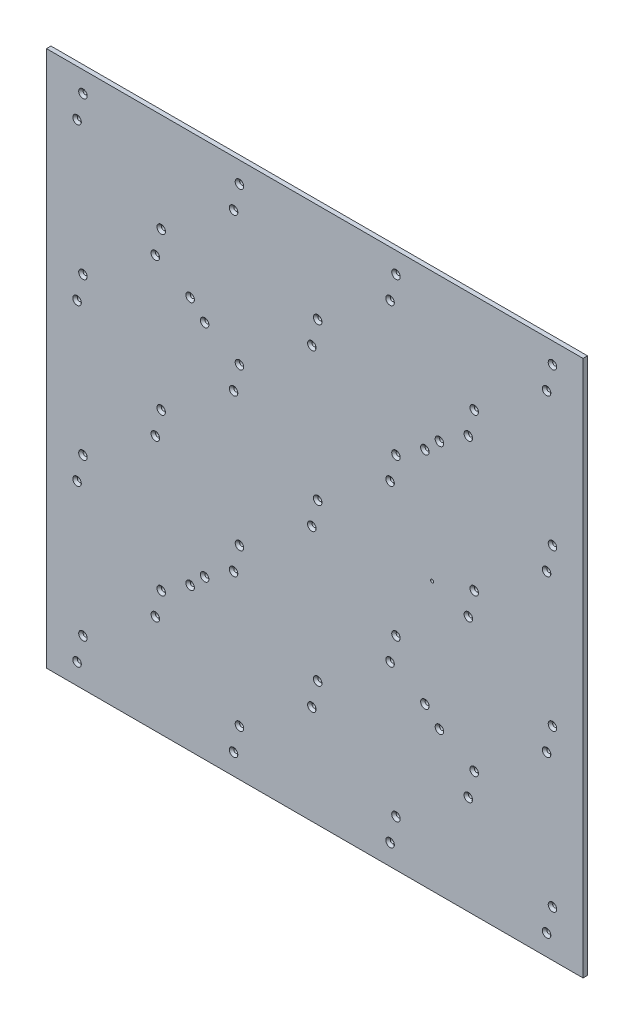
SolidWorks part; units mm, degrees
material "6063-T1"
ref_plane "Front Plane" through (0, 0, 0) normal (0, 0, 1) x (1, 0, 0)
ref_plane "Top Plane" through (0, 0, 0) normal (0, 1, 0) x (1, 0, 0)
ref_plane "Right Plane" through (0, 0, 0) normal (1, 0, 0) x (0, 0, -1)
sketch "Sketch1" plane through (0, 0, 0) normal (0, 0, 1) x (1, 0, 0)
  line L1 (600, -600) -> (-600, -600)
  line L2 (600, -600) -> (600, 600)
  line L3 (600, 600) -> (-600, 600)
  line L4 (-600, -600) -> (-600, 600)
  line L5 (600, -600) -> (-600, 600) construction
  line L6 (600, 600) -> (-600, -600) construction
  point P0 (0, 0)
  dimension "D1" = 1200
  dimension "D2" = 1200
extrude "Boss-Extrude1" add sketch "Sketch1" against normal blind 10 from offset 3
sketch "Sketch2" plane through (0, 0, -7) normal (0, 0, -1) x (-1, 0, 0)
  line L0 (-261.4393, 263.5607) -> (-244.8089, 280.1911) construction
  line L1 (-259.318, 261.4393) -> (-263.5607, 265.682) construction
  line L2 (-268.1434, 303.5257) -> (-221.4743, 256.8566) construction
  circle A1 centre (-278.75, 278.7769) radius 4.5
  circle A2 centre (-246.2231, 246.25) radius 4.5
  circle A3 centre (246.25, 246.2231) radius 4.5
  circle A4 centre (278.7769, 278.75) radius 4.5
  circle A5 centre (246.2231, -246.25) radius 4.5
  circle A6 centre (278.75, -278.7769) radius 4.5
  circle A7 centre (-246.25, -246.2231) radius 4.5
  circle A8 centre (-278.7769, -278.75) radius 4.5
  circle A9 centre (-531.5817, 553.5131) radius 4.5
  circle A10 centre (-518.4295, 496.5203) radius 4.5
  circle A11 centre (-531.5817, 203.5094) radius 4.5
  circle A12 centre (-518.4295, 146.5166) radius 4.5
  circle A13 centre (-343.4276, 321.5185) radius 4.5
  circle A14 centre (-356.5798, 378.5113) radius 4.5
  circle A15 centre (-181.578, 553.5131) radius 4.5
  circle A16 centre (-168.4258, 496.5203) radius 4.5
  circle A17 centre (168.4258, 553.5131) radius 4.5
  circle A18 centre (181.578, 496.5203) radius 4.5
  circle A19 centre (-6.5761, 378.5113) radius 4.5
  circle A20 centre (6.5761, 321.5185) radius 4.5
  circle A21 centre (-181.578, 203.5094) radius 4.5
  circle A22 centre (-168.4258, 146.5166) radius 4.5
  circle A23 centre (-356.5798, 28.5075) radius 4.5
  circle A24 centre (-343.4276, -28.4853) radius 4.5
  circle A25 centre (-518.4295, -203.4871) radius 4.5
  circle A26 centre (-531.5817, -146.4943) radius 4.5
  circle A27 centre (-531.5817, -496.498) radius 4.5
  circle A28 centre (-518.4295, -553.4908) radius 4.5
  circle A29 centre (-356.5798, -321.4962) radius 4.5
  circle A30 centre (-343.4276, -378.489) radius 4.5
  circle A31 centre (-181.578, -146.4943) radius 4.5
  circle A32 centre (-168.4258, -203.4871) radius 4.5
  circle A33 centre (-6.5761, 28.5075) radius 4.5
  circle A34 centre (6.5761, -28.4853) radius 4.5
  circle A35 centre (168.4258, 203.5094) radius 4.5
  circle A36 centre (181.578, 146.5166) radius 4.5
  circle A37 centre (343.4276, 378.5113) radius 4.5
  circle A38 centre (356.5798, 321.5185) radius 4.5
  circle A39 centre (518.4295, 553.5131) radius 4.5
  circle A40 centre (531.5817, 496.5203) radius 4.5
  circle A41 centre (-181.578, -496.498) radius 4.5
  circle A42 centre (-168.4258, -553.4908) radius 4.5
  circle A43 centre (-6.5761, -321.4962) radius 4.5
  circle A44 centre (6.5761, -378.489) radius 4.5
  circle A45 centre (168.4258, -146.4943) radius 4.5
  circle A46 centre (181.578, -203.4871) radius 4.5
  circle A47 centre (343.4276, 28.5075) radius 4.5
  circle A48 centre (356.5798, -28.4853) radius 4.5
  circle A49 centre (518.4295, 203.5094) radius 4.5
  circle A50 centre (531.5817, 146.5166) radius 4.5
  circle A51 centre (168.4258, -496.498) radius 4.5
  circle A52 centre (181.578, -553.4908) radius 4.5
  circle A53 centre (343.4276, -321.4962) radius 4.5
  circle A54 centre (356.5798, -378.489) radius 4.5
  circle A55 centre (531.5817, -203.4871) radius 4.5
  circle A56 centre (518.4295, -146.4943) radius 4.5
  circle A57 centre (518.4295, -496.498) radius 4.5
  circle A58 centre (531.5817, -553.4908) radius 4.5
  point P25 (0, 0)
  dimension "D1" = 9
  dimension "D2" = 4
extrude "Cut-Extrude1" cut sketch "Sketch2" against normal through all
chamfer "Chamfer1" distance 5 angle 45 58 edges at (250.7231, 246.25, 3) (274.25, 278.7769, 3) (-241.75, 246.2231, 3) (-283.2769, 278.75, 3) (-241.7231, -246.25, 3) (-283.25, -278.7769, 3) (250.75, -246.2231, 3) (274.2769, -278.75, 3) (527.0817, 553.5131, 3) (513.9295, 496.5203, 3) (527.0817, 203.5094, 3) (513.9295, 146.5166, 3) (338.9276, 321.5185, 3) (352.0798, 378.5113, 3) (177.078, 553.5131, 3) (163.9258, 496.5203, 3) (-172.9258, 553.5131, 3) (-186.078, 496.5203, 3) (2.0761, 378.5113, 3) (-11.0761, 321.5185, 3) (177.078, 203.5094, 3) (163.9258, 146.5166, 3) (352.0798, 28.5075, 3) (338.9276, -28.4853, 3) (513.9295, -203.4871, 3) (527.0817, -146.4943, 3) (527.0817, -496.498, 3) (513.9295, -553.4908, 3) (352.0798, -321.4962, 3) (338.9276, -378.489, 3) (177.078, -146.4943, 3) (163.9258, -203.4871, 3) (2.0761, 28.5075, 3) (-11.0761, -28.4853, 3) (-172.9258, 203.5094, 3) (-186.078, 146.5166, 3) (-347.9276, 378.5113, 3) (-361.0798, 321.5185, 3) (-522.9295, 553.5131, 3) (-536.0817, 496.5203, 3) (177.078, -496.498, 3) (163.9258, -553.4908, 3) (2.0761, -321.4962, 3) (-11.0761, -378.489, 3) (-172.9258, -146.4943, 3) (-186.078, -203.4871, 3) (-347.9276, 28.5075, 3) (-361.0798, -28.4853, 3) (-522.9295, 203.5094, 3) (-536.0817, 146.5166, 3) (-172.9258, -496.498, 3) (-186.078, -553.4908, 3) (-347.9276, -321.4962, 3) (-361.0798, -378.489, 3) (-536.0817, -203.4871, 3) (-522.9295, -146.4943, 3) (-522.9295, -496.498, 3) (-536.0817, -553.4908, 3)
sketch "Sketch3" plane through (0, 0, -7) normal (0, 0, -1) x (-1, 0, 0)
  line L0 (0, 0) -> (-525, 0) construction
  circle A0 centre (-262.5, 0) radius 3.4
  dimension "D1" = 6.8
extrude "Cut-Extrude2" cut sketch "Sketch3" against normal up to next
sketch "Sketch5" plane through (0, 0, 3) normal (0, 0, 1) x (1, 0, 0)
  line L0 (-350, 525) -> (-350, -525) construction
  line L1 (-525, 525) -> (525, 525) construction
  line L2 (-525, 525) -> (-525, -525) construction
  line L3 (-525, -525) -> (525, -525) construction
  line L4 (525, 525) -> (525, -525) construction
  line L5 (-525, 525) -> (525, -525) construction
  line L6 (-525, -525) -> (525, 525) construction
  line L7 (-175, 525) -> (-175, -525) construction
  line L8 (0, 525) -> (0, -525) construction
  line L9 (175, 525) -> (175, -525) construction
  line L10 (350, 525) -> (350, -525) construction
  line L11 (-525, 350) -> (525, 350) construction
  line L12 (-525, 175) -> (525, 175) construction
  line L13 (-525, 0) -> (525, 0) construction
  line L14 (-525, -175) -> (525, -175) construction
  line L15 (-525, -350) -> (525, -350) construction
  line L16 (175, 350) -> (350, 175) construction
  line L17 (350, -175) -> (175, -350) construction
  line L18 (-175, -350) -> (-350, -175) construction
  line L19 (-350, 175) -> (-175, 350) construction
  line L21 (339.3934, -45.9619) -> (304.0381, -10.6066) construction
  line L22 (339.3934, -45.9619) -> (395.9619, 10.6066) construction
  line L23 (395.9619, 10.6066) -> (360.6066, 45.9619) construction
  line L24 (304.0381, -10.6066) -> (360.6066, 45.9619) construction
  line L25 (339.3934, -45.9619) -> (360.6066, 45.9619) construction
  line L26 (395.9619, 10.6066) -> (304.0381, -10.6066) construction
  point P0 (0, 0)
  point P30 (350, 0)
  point P37 (0, 0)
  dimension "D1" = 1050
  dimension "D3" = 175
  dimension "D5" = 175
  dimension "D7" = 50
  dimension "D8" = 80
  dimension "D2" = 6
  dimension "D4" = 6
  dimension "D6" = 4
